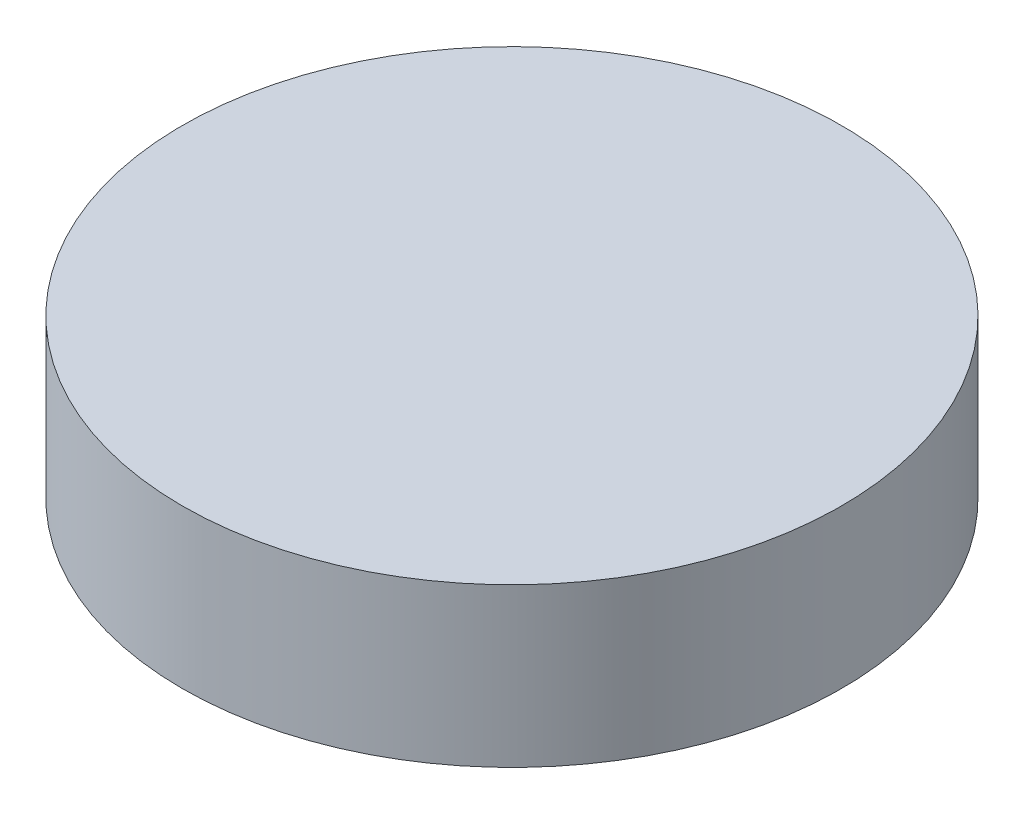
SolidWorks part; units mm, degrees
ref_plane "Front Plane" through (0, 0, 0) normal (0, 0, 1) x (1, 0, 0)
ref_plane "Top Plane" through (0, 0, 0) normal (0, 1, 0) x (1, 0, 0)
ref_plane "Right Plane" through (0, 0, 0) normal (1, 0, 0) x (0, 0, -1)
other "Configuration Table"
sketch "Sketch1" plane through (0, 0, 0) normal (0, 1, 0) x (1, 0, 0)
  circle A0 centre (50, 50) radius 25
extrude "OVEN_ayar_ayagi_1" add sketch "Sketch1" along normal blind 12 separate body
